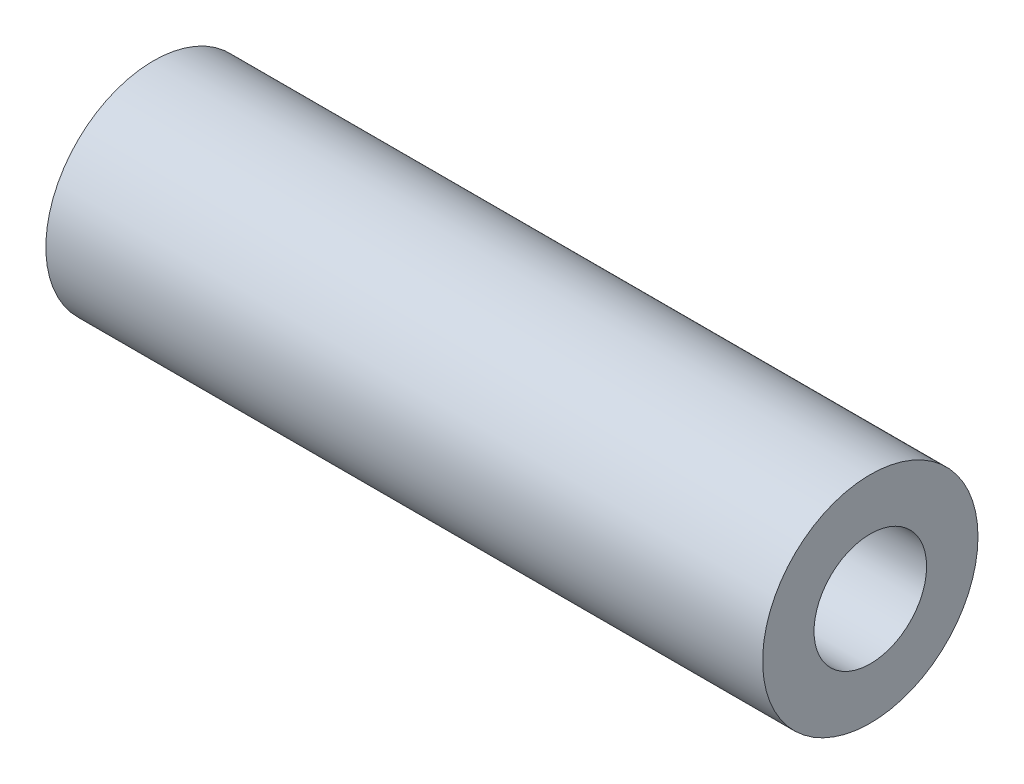
SolidWorks part; units mm, degrees
material "6061-T6 (SS)"
ref_plane "Front Plane" through (0, 0, 0) normal (0, 0, 1) x (1, 0, 0)
ref_plane "Top Plane" through (0, 0, 0) normal (0, 1, 0) x (1, 0, 0)
ref_plane "Right Plane" through (0, 0, 0) normal (1, 0, 0) x (0, 0, -1)
sketch "Sketch1" plane through (0, 0, 0) normal (1, 0, 0) x (0, 0, -1)
  circle A0 centre (0, 0) radius 4.7625
  circle A1 centre (0, 0) radius 2.4892
  dimension "D1" = 4.9784
  dimension "D2" = 9.525
extrude "Boss-Extrude1" add sketch "Sketch1" along normal mid plane 31.6992
